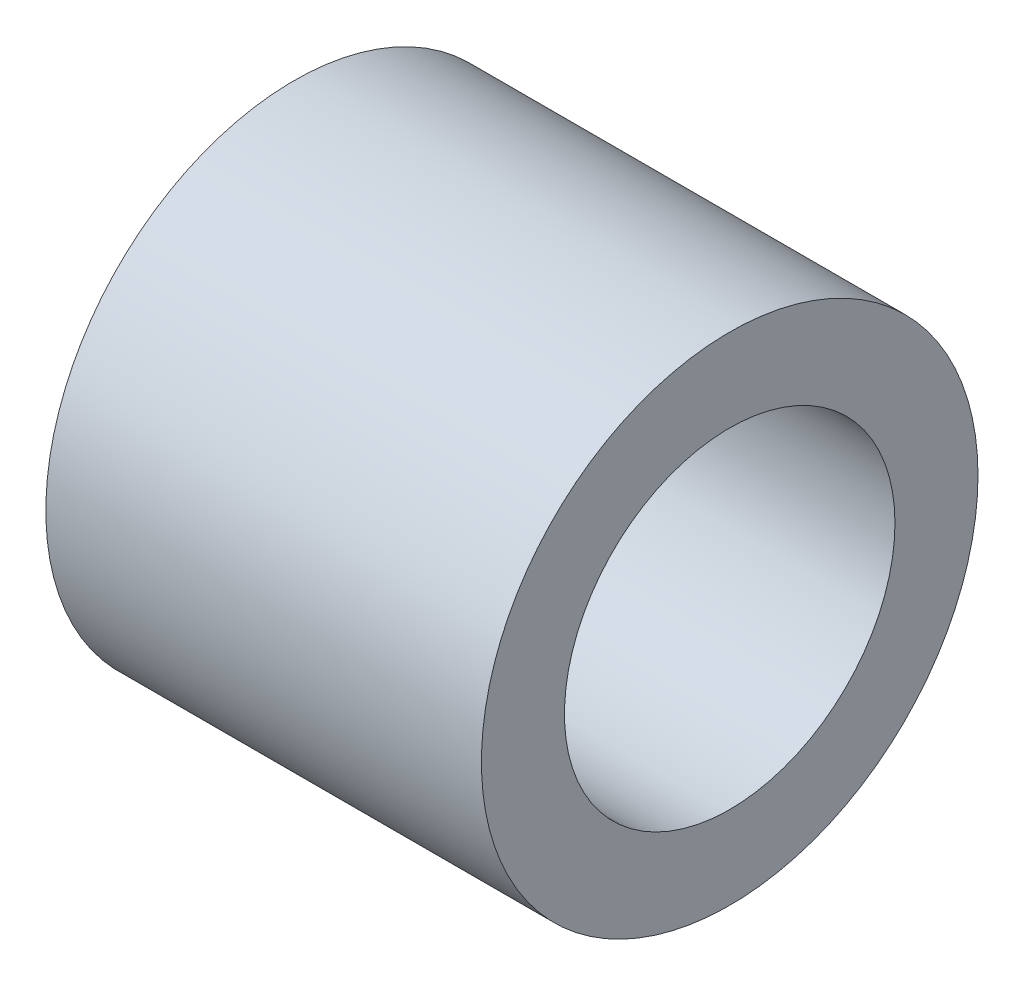
SolidWorks part; units mm, degrees
ref_plane "Front Plane" through (0, 0, 0) normal (0, 0, 1) x (1, 0, 0)
ref_plane "Top Plane" through (0, 0, 0) normal (0, 1, 0) x (1, 0, 0)
ref_plane "Right Plane" through (0, 0, 0) normal (1, 0, 0) x (0, 0, -1)
sketch "Sketch1" plane through (0, 0, 0) normal (1, 0, 0) x (0, 0, -1)
  circle A0 centre (0, 0) radius 2.65
  circle A1 centre (0, 0) radius 3.9815
  dimension "D1" = 5.3
  dimension "D2" = 7.9629
extrude "Boss-Extrude1" add sketch "Sketch1" along normal mid plane 6.985
